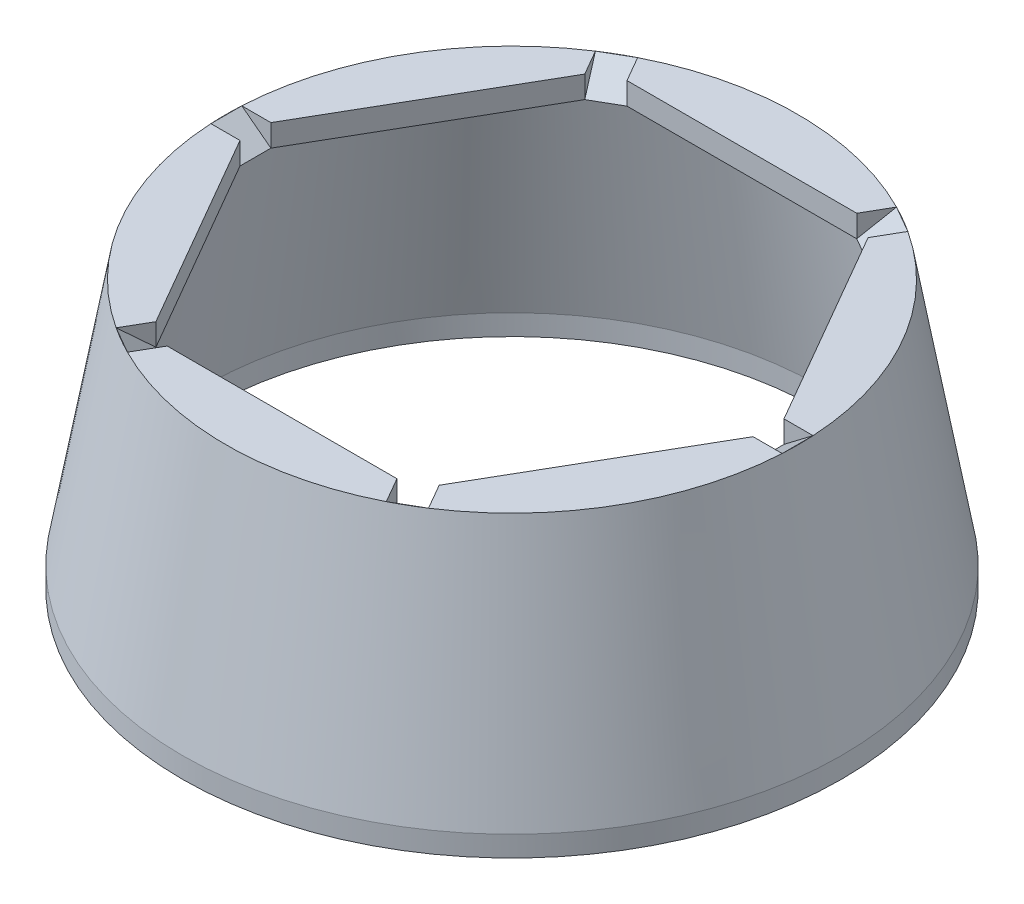
SolidWorks part; units mm, degrees
material "Ti-6Al-4VSolution treated and aged (SS)"
ref_plane "Front Plane" through (0, 0, 0) normal (0, 0, 1) x (1, 0, 0)
ref_plane "Top Plane" through (0, 0, 0) normal (0, 1, 0) x (1, 0, 0)
ref_plane "Right Plane" through (0, 0, 0) normal (1, 0, 0) x (0, 0, -1)
sketch "Sketch1" plane through (0, 0, 0) normal (0, 1, 0) x (1, 0, 0)
  circle A0 centre (0, 0) radius 800
  circle A1 centre (0, 0) radius 750
  dimension "D1" = 1600
  dimension "D2" = 50
extrude "Boss-Extrude1" add sketch "Sketch1" along normal blind 50
sketch "Sketch14" plane through (0, 0, 0) normal (1, 0, 0) x (0, 0, -1)
  line L0 (-800, 50) -> (-750, 50)
  line L1 (-800, 50) -> (-694.2038, 650)
  line L2 (-694.2038, 650) -> (-644.2038, 650)
  line L3 (-644.2038, 650) -> (-750, 50)
  line L4 (0, 0) -> (0, 657.8819)
  dimension "D1" = 80
  dimension "D2" = 600
revolve "Revolve1" add sketch "Sketch14" angle 360 about L4
sketch "Sketch15" plane through (0, 650, 0) normal (0, 1, 0) x (1, 0, 0)
  line L0 (278.8006, 557.8969) -> (343.7525, 520.3969)
  line L1 (622.5532, 37.5) -> (343.7525, 520.3969)
  line L2 (278.8006, 557.8969) -> (-278.8006, 557.8969)
  line L3 (-343.7525, 520.3969) -> (-622.5532, 37.5)
  line L4 (-622.5532, -37.5) -> (-343.7525, -520.3969)
  line L5 (-278.8006, -557.8969) -> (278.8006, -557.8969)
  line L6 (343.7525, -520.3969) -> (622.5532, -37.5)
  line L7 (622.5532, 37.5) -> (622.5532, -37.5)
  line L8 (343.7525, -520.3969) -> (278.8006, -557.8969)
  line L9 (-278.8006, -557.8969) -> (-343.7525, -520.3969)
  line L10 (-622.5532, -37.5) -> (-622.5532, 37.5)
  line L11 (-343.7525, 520.3969) -> (-278.8006, 557.8969)
  circle A0 centre (0, 0) radius 557.8969 construction
  circle A1 centre (0, 0) radius 694.2038
  point P25 (0, 0)
  dimension "D2" = 1388.4076
  dimension "D3" = 30
  dimension "D4" = 75
  dimension "D5" = 6
extrude "Boss-Extrude2" add sketch "Sketch15" against normal blind 53.6942
sketch "Sketch17" plane through (0, 0, 0) normal (0, 0, 1) x (1, 0, 0)
  line L0 (622.5532, 550) -> (819.8847, 700)
  line L1 (819.8847, 700) -> (622.5532, 700)
  line L2 (622.5532, 700) -> (622.5532, 550)
  dimension "D1" = 37.24
  dimension "D2" = 550
  dimension "D3" = 622.5532
  dimension "D4" = 150
sketch "Sketch18" plane through (0, 650, 0) normal (0, 1, 0) x (1, 0, 0)
  line L0 (622.5532, 37.5) -> (622.5532, -37.5)
  line L1 (622.5532, -37.5) -> (693.1902, -37.5)
  line L2 (693.1902, -37.5) -> (693.1902, 37.5)
  line L3 (693.1902, 37.5) -> (622.5532, 37.5)
  circle A1 centre (0, 0) radius 694.2038 construction
extrude "Cut-Extrude4" cut sketch "Sketch18" along direction (0.7961, 0.6052, 0) on the side against the normal blind 130
pattern_circular "CirPattern1" count 6 over 360 about axis through (0, 0, 0) along (0, 1, 0) of "Cut-Extrude4"
